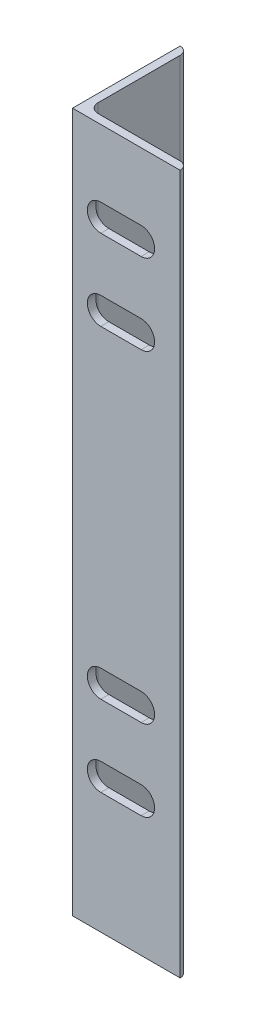
SolidWorks part; units mm, degrees
ref_plane "Front Plane" through (0, 0, 0) normal (0, 0, 1) x (1, 0, 0)
ref_plane "Top Plane" through (0, 0, 0) normal (0, 1, 0) x (1, 0, 0)
ref_plane "Right Plane" through (0, 0, 0) normal (1, 0, 0) x (0, 0, -1)
sketch3d "3DSketch1"
  line L0 (0, 0, 0) -> (0, 260, 0)
  dimension "D1" = 260
other "Iron V40X40X3(1)"
ref_plane "Plane1" through (0, 0, 0) normal (0, 1, 0) x (1, 0, 0)
sketch "Sketch1" plane through (0, 0, 0) normal (0, 1, 0) x (1, 0, 0)
  line L0 (0, 0) -> (0, 40)
  line L1 (0, 20) -> (3, 20) construction
  line L2 (3, 37) -> (3, 6.5)
  line L3 (6.5, 3) -> (37, 3)
  line L4 (20, 3) -> (20, 0) construction
  line L5 (40, 0) -> (0, 0)
  arc A0 (40, 0) -> (37, 3) centre (37, 0) ccw
  arc A1 (0, 40) -> (3, 37) centre (0, 37) cw
  arc A2 (6.5, 3) -> (3, 6.5) centre (6.5, 6.5) cw
  point P10 (20, 0)
  point P14 (0, 20)
  point P15 (3, 20)
  point P16 (20, 3)
  point P17 (3, 40)
  point P18 (40, 3)
  point P21 (0, 0)
  dimension "D2" = 3
  dimension "D3" = 40
  dimension "Radius_1" = 3.5
  dimension "D1" = 3
sketch "Sketch2" plane through (0, 0, 0) normal (0, 0, 1) x (1, 0, 0)
  line L0 (10.5, 50) -> (25.5, 50) construction
  line L1 (10.5, 55) -> (25.5, 55)
  line L2 (10.5, 45) -> (25.5, 45)
  line L3 (0, 0) -> (40, 0) construction
  line L4 (0, 0) -> (0, 260) construction
  line L5 (10.5, 80) -> (25.5, 80) construction
  line L6 (10.5, 85) -> (25.5, 85)
  line L7 (10.5, 75) -> (25.5, 75)
  line L8 (10.5, 200) -> (25.5, 200) construction
  line L9 (10.5, 205) -> (25.5, 205)
  line L10 (10.5, 195) -> (25.5, 195)
  line L11 (10.5, 230) -> (25.5, 230) construction
  line L12 (10.5, 235) -> (25.5, 235)
  line L13 (10.5, 225) -> (25.5, 225)
  arc A0 (10.5, 55) -> (10.5, 45) centre (10.5, 50) ccw
  arc A1 (25.5, 45) -> (25.5, 55) centre (25.5, 50) ccw
  arc A2 (10.5, 85) -> (10.5, 75) centre (10.5, 80) ccw
  arc A3 (25.5, 75) -> (25.5, 85) centre (25.5, 80) ccw
  arc A4 (10.5, 205) -> (10.5, 195) centre (10.5, 200) ccw
  arc A5 (25.5, 195) -> (25.5, 205) centre (25.5, 200) ccw
  arc A6 (10.5, 235) -> (10.5, 225) centre (10.5, 230) ccw
  arc A7 (25.5, 225) -> (25.5, 235) centre (25.5, 230) ccw
  point P2 (18, 50)
  point P14 (18, 80)
  point P22 (18, 200)
  point P29 (18, 230)
  dimension "D2" = 5
  dimension "D1" = 15
  dimension "D3" = 50
  dimension "D4" = 18
  dimension "D5" = 2
  dimension "D6" = 2
extrude "Cut-Extrude1" cut sketch "Sketch2" against normal blind 10
